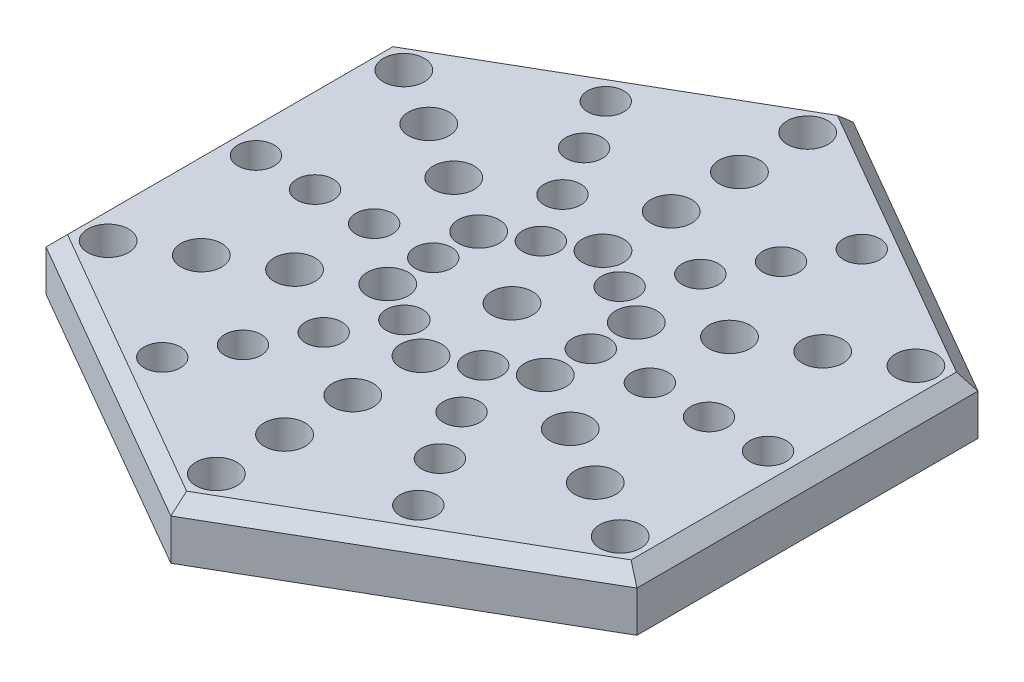
SolidWorks part; units mm, degrees
ref_plane "Plan de face" through (0, 0, 0) normal (0, 0, 1) x (1, 0, 0)
ref_plane "Plan de dessus" through (0, 0, 0) normal (0, 1, 0) x (1, 0, 0)
ref_plane "Plan de droite" through (0, 0, 0) normal (1, 0, 0) x (0, 0, -1)
sketch "Esquisse1" plane through (0, 0, 0) normal (0, 1, 0) x (1, 0, 0)
  line L0 (0, 0) -> (0, -75)
  line L7 (0, 0) -> (0, 20)
  line L8 (0, 20) -> (0, 35)
  line L9 (0, 35) -> (0, 50)
  line L10 (0, 50) -> (0, 65)
  line L11 (17.3205, 10) -> (17.3205, -10)
  line L12 (0, -75) -> (64.9519, -37.5)
  line L13 (64.9519, -37.5) -> (64.9519, 37.5)
  line L14 (64.9519, 37.5) -> (0, 75)
  line L15 (0, 75) -> (-64.9519, 37.5)
  line L16 (-64.9519, 37.5) -> (-64.9519, -37.5)
  line L17 (-64.9519, -37.5) -> (0, -75)
  line L18 (30.3109, 17.5) -> (30.3109, -17.5)
  line L19 (43.3013, 25) -> (43.3013, -25)
  line L20 (56.2917, 32.5) -> (56.2917, -32.5)
  circle A0 centre (0, 0) radius 64.9519 construction
  circle A1 centre (0, 0) radius 4.5
  circle A2 centre (0, 20) radius 4.5
  circle A3 centre (0, 35) radius 4.5
  circle A4 centre (0, 50) radius 4.5
  circle A5 centre (0, 65) radius 4.5
  circle A6 centre (0, 0) radius 4.5
  circle A7 centre (17.3205, 10) radius 4.5
  circle A8 centre (30.3109, 17.5) radius 4.5
  circle A9 centre (43.3013, 25) radius 4.5
  circle A10 centre (56.2917, 32.5) radius 4.5
  circle A11 centre (0, 0) radius 4.5
  circle A12 centre (17.3205, -10) radius 4.5
  circle A13 centre (30.3109, -17.5) radius 4.5
  circle A14 centre (43.3013, -25) radius 4.5
  circle A15 centre (56.2917, -32.5) radius 4.5
  circle A16 centre (0, 0) radius 4.5
  circle A17 centre (0, -20) radius 4.5
  circle A18 centre (0, -35) radius 4.5
  circle A19 centre (0, -50) radius 4.5
  circle A20 centre (0, -65) radius 4.5
  circle A21 centre (0, 0) radius 4.5
  circle A22 centre (-17.3205, -10) radius 4.5
  circle A23 centre (-30.3109, -17.5) radius 4.5
  circle A24 centre (-43.3013, -25) radius 4.5
  circle A25 centre (-56.2917, -32.5) radius 4.5
  circle A26 centre (0, 0) radius 4.5
  circle A27 centre (-17.3205, 10) radius 4.5
  circle A28 centre (-30.3109, 17.5) radius 4.5
  circle A29 centre (-43.3013, 25) radius 4.5
  circle A30 centre (-56.2917, 32.5) radius 4.5
  circle A31 centre (17.3205, 0) radius 4
  circle A32 centre (30.3109, 0) radius 4
  circle A33 centre (43.3013, 0) radius 4
  circle A34 centre (56.2917, 0) radius 4
  circle A35 centre (8.6603, -15) radius 4
  circle A36 centre (15.1554, -26.25) radius 4
  circle A37 centre (21.6506, -37.5) radius 4
  circle A38 centre (28.1458, -48.75) radius 4
  circle A39 centre (-8.6603, -15) radius 4
  circle A40 centre (-15.1554, -26.25) radius 4
  circle A41 centre (-21.6506, -37.5) radius 4
  circle A42 centre (-28.1458, -48.75) radius 4
  circle A43 centre (-17.3205, 0) radius 4
  circle A44 centre (-30.3109, 0) radius 4
  circle A45 centre (-43.3013, 0) radius 4
  circle A46 centre (-56.2917, 0) radius 4
  circle A47 centre (-8.6603, 15) radius 4
  circle A48 centre (-15.1554, 26.25) radius 4
  circle A49 centre (-21.6506, 37.5) radius 4
  circle A50 centre (-28.1458, 48.75) radius 4
  circle A51 centre (8.6603, 15) radius 4
  circle A52 centre (15.1554, 26.25) radius 4
  circle A53 centre (21.6506, 37.5) radius 4
  circle A54 centre (28.1458, 48.75) radius 4
  point P66 (0, 0)
  point P115 (0, 0)
  dimension "D2" = 9
  dimension "D4" = 9
  dimension "D8" = 9
  dimension "D9" = 9
  dimension "D10" = 9
  dimension "D13" = 8
  dimension "D14" = 8
  dimension "D15" = 8
  dimension "D16" = 8
  dimension "D3" = 20
  dimension "D5" = 15
  dimension "D6" = 15
  dimension "D7" = 15
  dimension "D12" = 75
  dimension "D11" = 6
  dimension "D17" = 6
extrude "Boss.-Extru.1" add sketch "Esquisse1" along normal blind 12
chamfer "Chanfrein1" distance 3 angle 45 6 edges at (32.476, 12, 56.25) (-32.476, 12, 56.25) (-64.9519, 12, 0) (-32.476, 12, -56.25) (32.476, 12, -56.25) (64.9519, 12, 0)
equation "\"diamètre\"=9"
equation "\"D2@Esquisse1\"=\"diamètre\""
equation "\"D4@Esquisse1\"=\"diamètre\""
equation "\"D8@Esquisse1\"=\"diamètre\""
equation "\"D9@Esquisse1\"=\"diamètre\""
equation "\"D10@Esquisse1\"=\"diamètre\""
equation "\"diamètre2\"=8"
equation "\"D13@Esquisse1\"=\"diamètre2\""
equation "\"D14@Esquisse1\"=\"diamètre2\""
equation "\"D15@Esquisse1\"=\"diamètre2\""
equation "\"D16@Esquisse1\"=\"diamètre2\""
